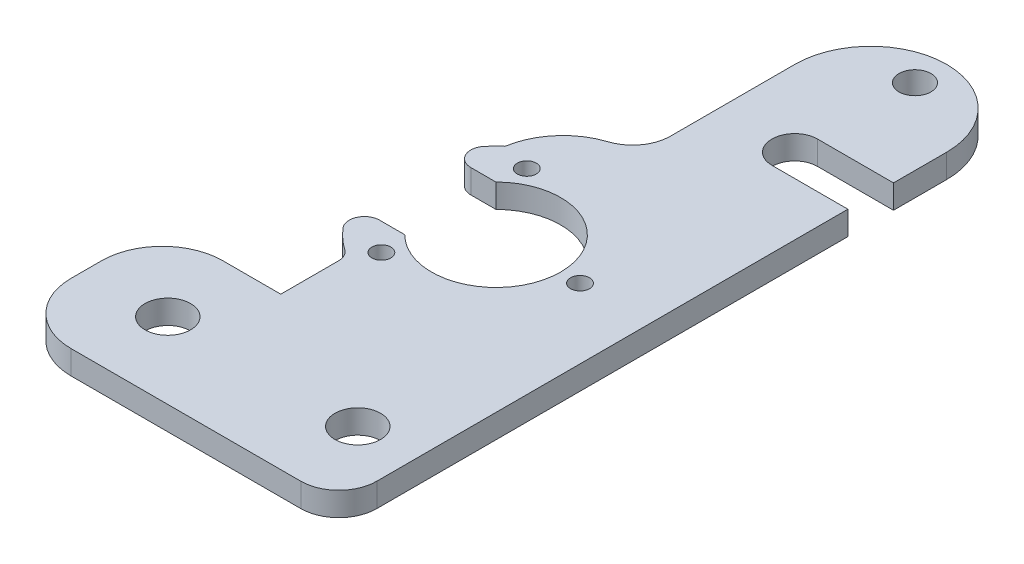
SolidWorks part; units mm, degrees
material "6061 Alloy"
ref_plane "Front Plane" through (0, 0, 0) normal (0, 0, 1) x (1, 0, 0)
ref_plane "Top Plane" through (0, 0, 0) normal (0, 1, 0) x (1, 0, 0)
ref_plane "Right Plane" through (0, 0, 0) normal (1, 0, 0) x (0, 0, -1)
ref_plane "Plane1" through (0, 108.6504, 0) normal (0, -1, 0) x (1, 0, 0)
sketch "Sketch1" plane through (0, 108.6504, 0) normal (0, -1, 0) x (1, 0, 0)
  line L0 (43.2375, 110.0333) -> (43.2375, 185.038)
  line L1 (38.2375, 190.038) -> (8, 190.038)
  line L2 (0, 182.038) -> (0, 178.038)
  line L3 (8, 170.038) -> (15.604, 170.038)
  line L4 (15.604, 170.038) -> (15.604, 162.4051)
  line L5 (13.6735, 155.101) -> (16.9792, 155.101)
  line L6 (16.9792, 143.101) -> (13.6735, 143.101)
  line L7 (23.2375, 126.368) -> (23.2375, 110.0333)
  arc A0 (43.2375, 185.038) -> (38.2375, 190.038) centre (38.2375, 185.038) ccw
  arc A1 (8, 190.038) -> (0, 182.038) centre (8, 182.038) ccw
  arc A2 (0, 178.038) -> (8, 170.038) centre (8, 178.038) ccw
  arc A3 (15.604, 162.4051) -> (14.7578, 160.7714) centre (13.604, 162.4051) cw
  arc A4 (14.7578, 160.7714) -> (12.1555, 158.4031) centre (23, 149.101) ccw
  arc A5 (12.1555, 158.4031) -> (13.6735, 155.101) centre (13.6735, 157.101) ccw
  arc A6 (16.9792, 155.101) -> (16.9792, 143.101) centre (23, 149.101) cw
  arc A7 (13.6735, 143.101) -> (12.1555, 139.7989) centre (13.6735, 141.101) ccw
  arc A8 (12.1555, 139.7989) -> (13.5108, 138.4198) centre (23, 149.101) ccw
  arc A9 (13.5108, 138.4198) -> (19.7744, 131.126) centre (22.6068, 139.8946) ccw
  arc A10 (19.7744, 131.126) -> (23.2375, 126.368) centre (18.2375, 126.368) cw
  arc A11 (23.2375, 110.0333) -> (43.2375, 110.0333) centre (33.2375, 110.0333) ccw
extrude "Boss-Extrude1" add sketch "Sketch1" against normal blind 3.125
sketch "Sketch2" plane through (0, 111.7754, 0) normal (0, 1, 0) x (-1, 0, 0)
  line L0 (-43.2375, 123.038) -> (-43.2375, 117.038)
  line L1 (-43.2375, 117.038) -> (-33.2375, 117.038)
  line L2 (-33.2375, 123.038) -> (-43.2375, 123.038)
  arc A0 (-33.2375, 117.038) -> (-33.2375, 123.038) centre (-33.2375, 120.038) ccw
extrude "Cut-Extrude1" cut sketch "Sketch2" against normal through all
hole_wizard "Ø6.0 (6) Diameter Hole1" positions "Sketch4" profile "Sketch3" hole size "Ø6.0" standard "ANSI Metric"
sketch "Sketch4" plane through (0, 108.6504, 0) normal (0, -1, 0) x (-1, 0, 0)
  point P0 (-10.7375, -180.038)
  point P1 (-35.7375, -180.038)
sketch "Sketch3" plane through (10.7375, 108.6504, 180.038) normal (1, 0, 0) x (0, 0, -1)
  line L0 (0, 0) -> (0, 3.125)
  line L1 (0, 3.125) -> (3, 3.125)
  line L2 (3, 3.125) -> (3, 0)
  line L5 (3, 0) -> (0, 0)
  line L11 (0, -6.35) -> (0, 107.95) construction
  dimension "Thru Hole Dia." = 6
  dimension "Thru Hole Depth" = 3.125
hole_wizard "Ø2.5 (2.5) Diameter Hole1" positions "Sketch6" profile "Sketch5" hole size "Ø2.5" standard "ANSI Metric"
sketch "Sketch6" plane through (0, 108.6504, 0) normal (0, -1, 0) x (-1, 0, 0)
  point P0 (-34.049, -149.101)
  point P1 (-17.4755, -158.6697)
  point P2 (-17.4755, -139.5323)
sketch "Sketch5" plane through (34.049, 108.6504, 149.101) normal (1, 0, 0) x (0, 0, -1)
  line L0 (0, 0) -> (0, 3.125)
  line L1 (0, 3.125) -> (1.25, 3.125)
  line L2 (1.25, 3.125) -> (1.25, 0)
  line L5 (1.25, 0) -> (0, 0)
  line L11 (0, -6.35) -> (0, 107.95) construction
  dimension "Thru Hole Dia." = 2.5
  dimension "Thru Hole Depth" = 3.125
hole_wizard "Ø4.2 (4.2) Diameter Hole1" positions "Sketch8" profile "Sketch7" hole size "Ø4.2" standard "ANSI Metric"
sketch "Sketch8" plane through (0, 108.6504, 0) normal (0, -1, 0) x (-1, 0, 0)
  point P0 (-33.2375, -104.2117)
sketch "Sketch7" plane through (33.2375, 108.6504, 104.2117) normal (1, 0, 0) x (0, 0, -1)
  line L0 (0, 0) -> (0, 3.125)
  line L1 (0, 3.125) -> (2.1, 3.125)
  line L2 (2.1, 3.125) -> (2.1, 0)
  line L5 (2.1, 0) -> (0, 0)
  line L11 (0, -6.35) -> (0, 107.95) construction
  dimension "Thru Hole Dia." = 4.2
  dimension "Thru Hole Depth" = 3.125
ref_point "Point1"
ref_point "Point2"
ref_plane "Plane2" through (0, 0, 180.038) normal (0, 0, 1) x (1, 0, 0)
ref_plane "Plane3" through (0, 0, 120.038) normal (0, 0, -1) x (-1, 0, 0)
